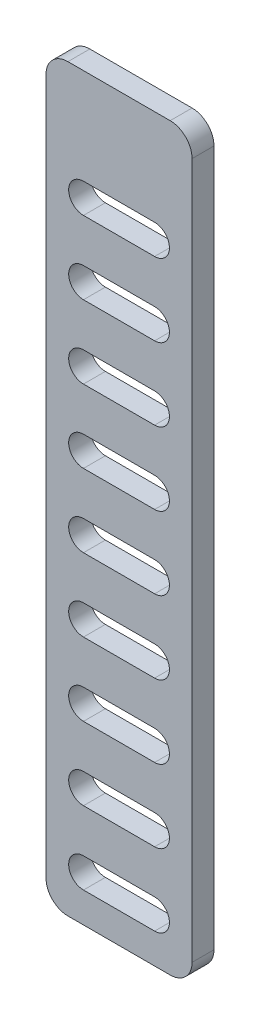
SolidWorks part; units mm, degrees
material "Alloy Steel"
ref_plane "Front Plane" through (0, 0, 0) normal (0, 0, 1) x (1, 0, 0)
ref_plane "Top Plane" through (0, 0, 0) normal (0, 1, 0) x (1, 0, 0)
ref_plane "Right Plane" through (0, 0, 0) normal (1, 0, 0) x (0, 0, -1)
sketch "Sketch1" plane through (0, 0, 0) normal (0, 0, 1) x (1, 0, 0)
  line L6 (-81.0668, 33.9086) -> (-101.0668, 33.9086)
  line L7 (-81.0668, 135.224) -> (-101.0668, 135.224)
  line L8 (-91.0668, 24.5794) -> (-91.0668, 142.0861) construction
  line L9 (-86.196, 40.0812) -> (-95.9377, 40.0812) construction
  line L10 (-101.0668, 135.224) -> (-101.0668, 33.9086)
  line L11 (-81.0668, 135.224) -> (-81.0668, 33.9086)
  line L12 (-86.196, 38.0536) -> (-95.9377, 38.0536)
  line L13 (-86.196, 42.1089) -> (-95.9377, 42.1089)
  line L14 (-86.196, 50.0812) -> (-95.9377, 50.0812) construction
  line L15 (-86.196, 48.0536) -> (-95.9377, 48.0536)
  line L16 (-86.196, 52.1089) -> (-95.9377, 52.1089)
  line L17 (-86.196, 60.0812) -> (-95.9377, 60.0812) construction
  line L20 (-86.196, 58.0536) -> (-95.9377, 58.0536)
  line L23 (-86.196, 62.1089) -> (-95.9377, 62.1089)
  line L26 (-86.196, 70.0812) -> (-95.9377, 70.0812) construction
  line L29 (-86.196, 68.0536) -> (-95.9377, 68.0536)
  line L32 (-86.196, 72.1089) -> (-95.9377, 72.1089)
  line L35 (-86.196, 80.0812) -> (-95.9377, 80.0812) construction
  line L38 (-86.196, 78.0536) -> (-95.9377, 78.0536)
  line L39 (-86.196, 82.1089) -> (-95.9377, 82.1089)
  line L40 (-86.196, 90.0812) -> (-95.9377, 90.0812) construction
  line L41 (-86.196, 88.0536) -> (-95.9377, 88.0536)
  line L42 (-86.196, 92.1089) -> (-95.9377, 92.1089)
  line L43 (-86.196, 100.0812) -> (-95.9377, 100.0812) construction
  line L44 (-86.196, 98.0536) -> (-95.9377, 98.0536)
  line L45 (-86.196, 102.1089) -> (-95.9377, 102.1089)
  line L46 (-86.196, 110.0812) -> (-95.9377, 110.0812) construction
  line L47 (-86.196, 108.0536) -> (-95.9377, 108.0536)
  line L48 (-86.196, 112.1089) -> (-95.9377, 112.1089)
  line L49 (-86.196, 120.0812) -> (-95.9377, 120.0812) construction
  line L50 (-86.196, 118.0536) -> (-95.9377, 118.0536)
  line L51 (-86.196, 122.1089) -> (-95.9377, 122.1089)
  line L52 (-81.0668, 135.224) -> (-78.0668, 135.224) construction
  arc A0 (-86.196, 38.0536) -> (-86.196, 42.1089) centre (-86.196, 40.0812) ccw
  arc A1 (-95.9377, 42.1089) -> (-95.9377, 38.0536) centre (-95.9377, 40.0812) ccw
  arc A2 (-86.196, 48.0536) -> (-86.196, 52.1089) centre (-86.196, 50.0812) ccw
  arc A3 (-95.9377, 52.1089) -> (-95.9377, 48.0536) centre (-95.9377, 50.0812) ccw
  arc A18 (-86.196, 58.0536) -> (-86.196, 62.1089) centre (-86.196, 60.0812) ccw
  arc A19 (-95.9377, 62.1089) -> (-95.9377, 58.0536) centre (-95.9377, 60.0812) ccw
  arc A20 (-86.196, 68.0536) -> (-86.196, 72.1089) centre (-86.196, 70.0812) ccw
  arc A21 (-95.9377, 72.1089) -> (-95.9377, 68.0536) centre (-95.9377, 70.0812) ccw
  arc A22 (-86.196, 78.0536) -> (-86.196, 82.1089) centre (-86.196, 80.0812) ccw
  arc A23 (-95.9377, 82.1089) -> (-95.9377, 78.0536) centre (-95.9377, 80.0812) ccw
  arc A24 (-86.196, 88.0536) -> (-86.196, 92.1089) centre (-86.196, 90.0812) ccw
  arc A25 (-95.9377, 92.1089) -> (-95.9377, 88.0536) centre (-95.9377, 90.0812) ccw
  arc A26 (-86.196, 98.0536) -> (-86.196, 102.1089) centre (-86.196, 100.0812) ccw
  arc A27 (-95.9377, 102.1089) -> (-95.9377, 98.0536) centre (-95.9377, 100.0812) ccw
  arc A28 (-86.196, 108.0536) -> (-86.196, 112.1089) centre (-86.196, 110.0812) ccw
  arc A29 (-95.9377, 112.1089) -> (-95.9377, 108.0536) centre (-95.9377, 110.0812) ccw
  arc A30 (-86.196, 118.0536) -> (-86.196, 122.1089) centre (-86.196, 120.0812) ccw
  arc A31 (-95.9377, 122.1089) -> (-95.9377, 118.0536) centre (-95.9377, 120.0812) ccw
  point P8 (-91.0668, 40.0812)
  point P15 (-91.0668, 50.0812)
  point P23 (-91.0668, 60.0812)
  point P30 (-91.0668, 70.0812)
  point P37 (-91.0668, 80.0812)
  point P44 (-91.0668, 90.0812)
  point P51 (-91.0668, 100.0812)
  point P58 (-91.0668, 110.0812)
  point P65 (-91.0668, 120.0812)
  dimension "D1" = 10
  dimension "D3" = 20
  dimension "D4" = 10
  dimension "D2" = 8
extrude "Boss-Extrude1" add sketch "Sketch1" along normal blind 3
fillet "Fillet1" radius 3 4 edges at (-101.0668, 135.224, 1.5) (-81.0668, 135.224, 1.5) (-101.0668, 33.9086, 1.5) (-81.0668, 33.9086, 1.5)
